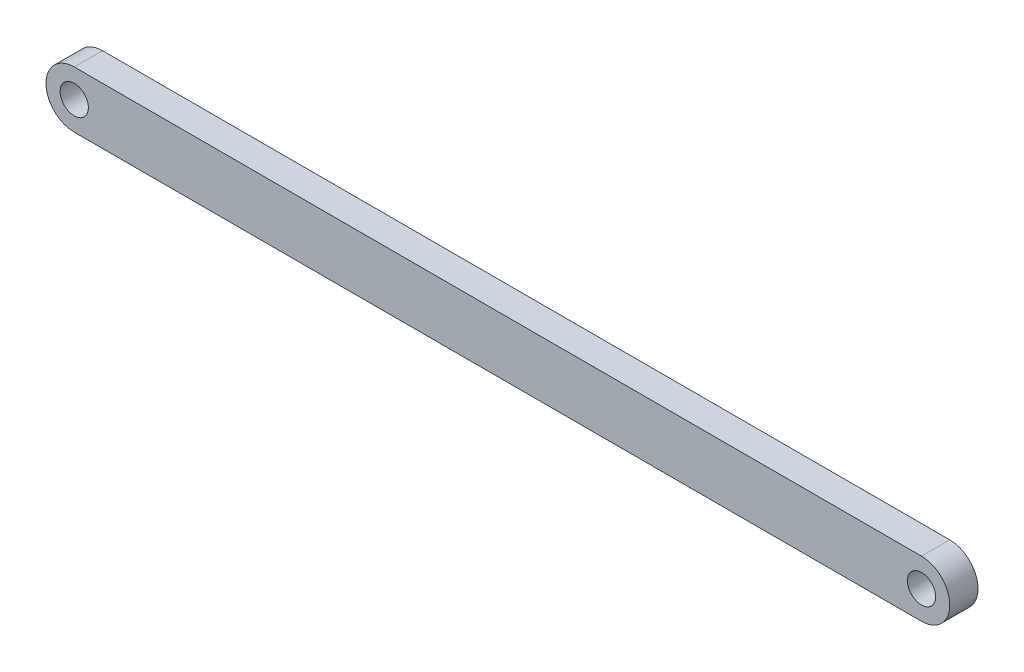
SolidWorks part; units mm, degrees
ref_plane "Plano frontal" through (0, 0, 0) normal (0, 0, 1) x (1, 0, 0)
ref_plane "Plano superior" through (0, 0, 0) normal (0, 1, 0) x (1, 0, 0)
ref_plane "Plano direito" through (0, 0, 0) normal (1, 0, 0) x (0, 0, -1)
sketch "Esboço1" plane through (0, 0, 0) normal (0, 0, 1) x (1, 0, 0)
  line L0 (-150, 10) -> (150, 10)
  line L1 (-192.079, 0) -> (182.6698, 0) construction
  line L2 (-150, -10) -> (150, -10)
  arc A0 (-150, 10) -> (-150, -10) centre (-150, 0) ccw
  arc A1 (150, 10) -> (150, -10) centre (150, 0) cw
  circle A2 centre (-150, 0) radius 5
  circle A3 centre (150, 0) radius 5
  point P3 (0, 10)
  dimension "D1" = 300
  dimension "D2" = 10
extrude "Ressalto-extrusão1" add sketch "Esboço1" along normal blind 10
